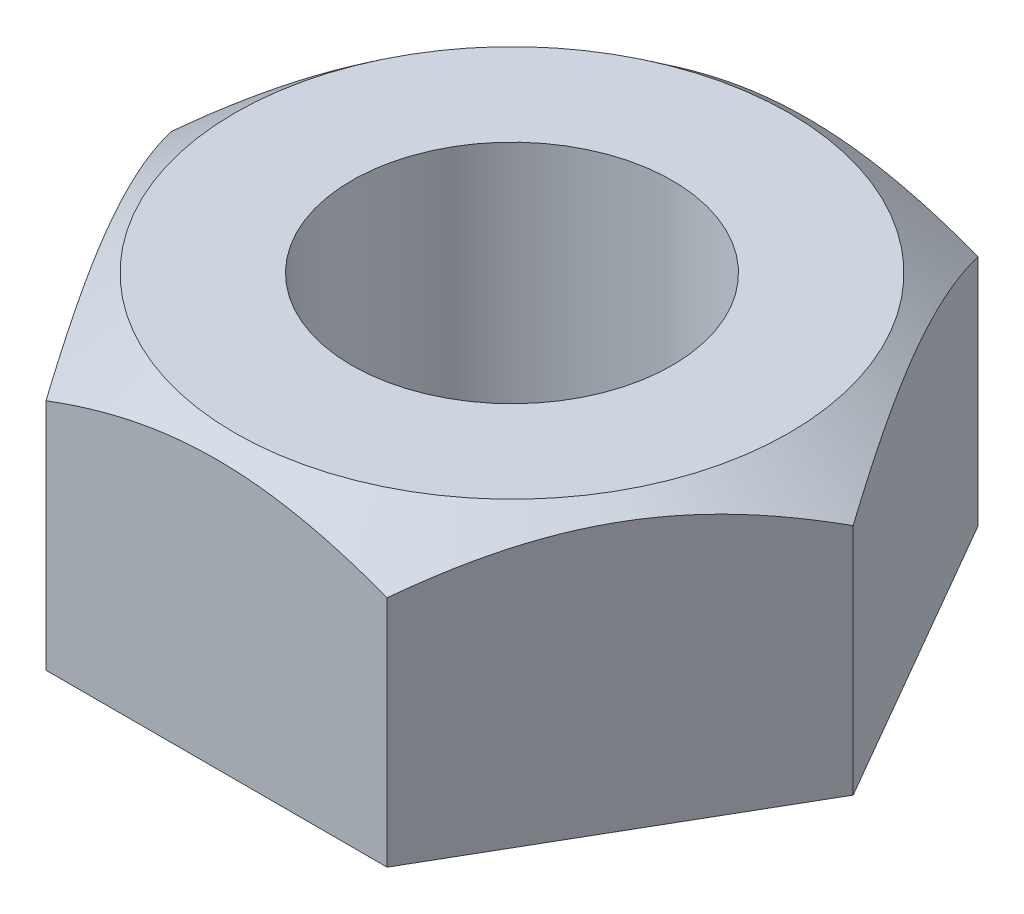
SolidWorks part; units mm, degrees
ref_plane "Front Plane" through (0, 0, 0) normal (0, 0, 1) x (1, 0, 0)
ref_plane "Top Plane" through (0, 0, 0) normal (0, 1, 0) x (1, 0, 0)
ref_plane "Right Plane" through (0, 0, 0) normal (1, 0, 0) x (0, 0, -1)
sketch "Sketch1" plane through (0, 0, 0) normal (0, 1, 0) x (1, 0, 0)
  line L1 (4.5784, 0) -> (2.2892, 3.965)
  line L2 (2.2892, 3.965) -> (-2.2892, 3.965)
  line L3 (-2.2892, 3.965) -> (-4.5784, 0)
  line L4 (-4.5784, 0) -> (-2.2892, -3.965)
  line L5 (-2.2892, -3.965) -> (2.2892, -3.965)
  line L6 (2.2892, -3.965) -> (4.5784, 0)
  circle A0 centre (0, 0) radius 3.965 construction
  circle A1 centre (0, 0) radius 2.15
  dimension "D2" = 4.3
  dimension "D1" = 7.93
extrude "Boss-Extrude1" add sketch "Sketch1" along normal blind 3.78
sketch "Sketch2" plane through (0, 0, 0) normal (1, 0, 0) x (0, 0, -1)
  line L0 (0, 0) -> (0, 3.78) construction
  line L1 (3.0084, 4.317) -> (7.7608, 0.7303)
  line L2 (7.7608, 0.7303) -> (8.8612, 2.98)
  line L3 (8.8612, 2.98) -> (3.0084, 4.317)
revolve "Cut-Revolve1" cut sketch "Sketch2" angle 360 about L0
